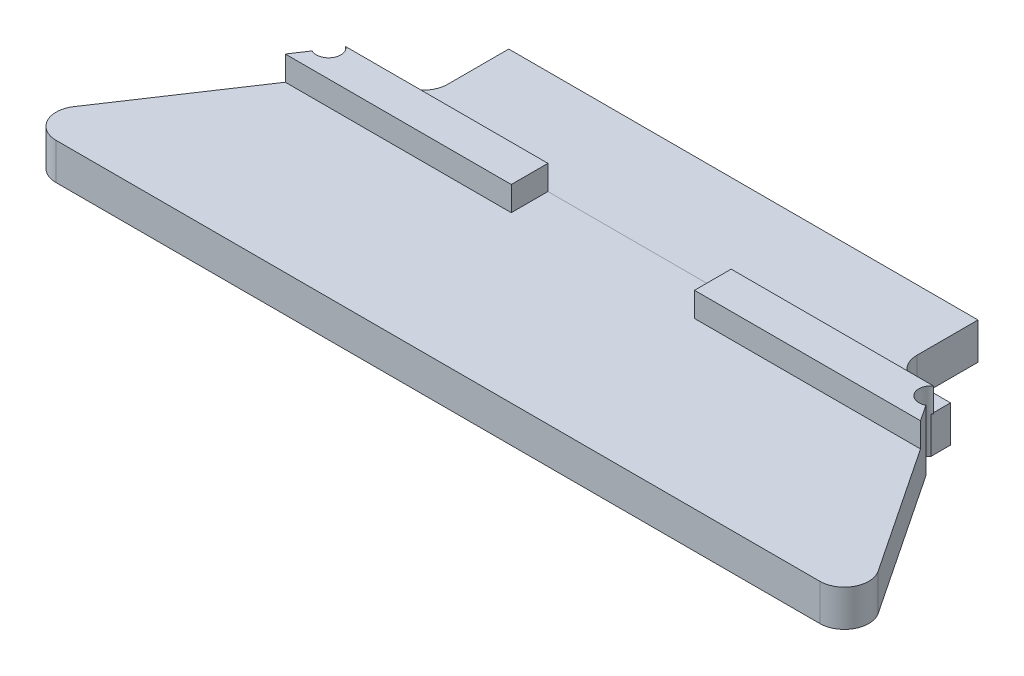
SolidWorks part; units mm, degrees
material "99.5% Aluminum Oxide"
ref_plane "Front Plane" through (0, 0, 0) normal (0, 0, 1) x (1, 0, 0)
ref_plane "Top Plane" through (0, 0, 0) normal (0, 1, 0) x (1, 0, 0)
ref_plane "Right Plane" through (0, 0, 0) normal (1, 0, 0) x (0, 0, -1)
sketch "Sketch1" plane through (0, 0, 0) normal (0, 1, 0) x (1, 0, 0)
  line L1 (-25, -12.5) -> (25, -12.5)
  line L2 (-25, -12.5) -> (-25, 12.5) construction
  line L3 (-25, 12.5) -> (25, 12.5) construction
  line L4 (25, -12.5) -> (25, 12.5) construction
  line L5 (-25, -12.5) -> (25, 12.5) construction
  line L6 (-25, 12.5) -> (25, -12.5) construction
  line L8 (-19.2062, 12.5) -> (19.2062, 12.5)
  line L11 (0, 11.2271) -> (0, -49988.7729) construction
  line L12 (-24.2062, 2.5) -> (-25, 2.5)
  line L13 (24.2062, 2.5) -> (25, 2.5)
  line L14 (-25, 2.5) -> (-35, -12.5)
  line L15 (-35, -12.5) -> (-25, -12.5)
  line L16 (25, 2.5) -> (35, -12.5)
  line L17 (35, -12.5) -> (25, -12.5)
  line L18 (-24.2062, 2.5) -> (-24.2062, 5.5)
  line L19 (-24.2062, 5.5) -> (-19.2062, 5.5)
  line L20 (-19.2062, 5.5) -> (-19.2062, 12.5)
  line L21 (24.2062, 2.5) -> (24.2062, 5.5)
  line L22 (24.2062, 5.5) -> (19.2062, 5.5)
  line L23 (19.2062, 5.5) -> (19.2062, 12.5)
  point P0 (0, 0)
  point P14 (0, 12.5)
  dimension "D1" = 25
  dimension "D2" = 50
  dimension "D3" = 10
  dimension "D4" = 15
  dimension "D5" = 0.7937
  dimension "D6" = 3
  dimension "D7" = 5
extrude "Boss-Extrude1" add sketch "Sketch1" along normal mid plane 3
sketch "Sketch4" plane through (0, 1.5, 0) normal (0, 1, 0) x (1, 0, 0)
  line L0 (-24.2062, 2.5) -> (-25, 2.5) construction
  line L2 (24.2062, 2.5) -> (23.9562, 2.5)
  line L3 (0, 0) -> (0, 50000) construction
  line L4 (-24.2062, 5.5) -> (-23.9562, 5.5)
  line L5 (-24.2062, 5.5) -> (-24.2062, 2.5)
  line L6 (-24.2062, 2.5) -> (-23.9562, 2.5)
  line L7 (-23.9562, 5.5) -> (-23.9562, 2.5)
  line L12 (23.9562, 5.5) -> (23.9562, 2.5)
  line L13 (24.2062, 5.5) -> (23.9562, 5.5)
  line L14 (24.2062, 5.5) -> (24.2062, 2.5)
  dimension "D1" = 0.25
extrude "Cut-Extrude4" cut sketch "Sketch4" against normal through all both and the other way through all
sketch "Sketch5" plane through (0, 1.5, 0) normal (0, 1, 0) x (1, 0, 0)
  line L0 (-23.9562, 2.5) -> (-24.6634, 3.2071) construction
  line L1 (-23.9562, 2.5) -> (-23.9562, 5.5) construction
  line L2 (-23.9562, 2.5) -> (-25, 2.5) construction
  line L3 (0, 0) -> (0, 50000) construction
  circle A0 centre (-24.6634, 3.2071) radius 1
  circle A1 centre (24.6634, 3.2071) radius 1
  point P2 (-23.9562, 3.9142)
  point P3 (-25.3705, 2.5)
  point P4 (-23.9562, 2.5)
  dimension "D1" = 2
  dimension "D2" = 45
extrude "Cut-Extrude5" cut sketch "Sketch5" against normal through all both and the other way through all
fillet "Fillet5" radius 2 4 edges at (35, 0, 12.5) (-35, 0, 12.5) (19.2062, 0, -5.5) (-19.2062, 0, -5.5)
sketch "Sketch6" plane through (0, 1.5, 0) normal (0, 1, 0) x (1, 0, 0)
  line L1 (-24.054, 4) -> (-7.5, 4)
  line L2 (-7.5, 4) -> (-7.5, 1)
  line L3 (-7.5, 1) -> (-26, 1)
  line L5 (-25.1213, 2.3181) -> (-26, 1)
  line L6 (-25.1213, 2.3181) -> (-32.9271, -9.3906) construction
  line L8 (32.9271, -9.3906) -> (25.1213, 2.3181) construction
  line L9 (26, 1) -> (25.1213, 2.3181)
  line L10 (24.054, 4) -> (7.5, 4)
  line L11 (7.5, 4) -> (7.5, 1)
  line L12 (7.5, 1) -> (26, 1)
  line L13 (19.2062, 12.5) -> (-19.2062, 12.5) construction
  arc A0 (-25.1213, 2.3181) -> (-23.9562, 3.9142) centre (-24.6634, 3.2071) ccw construction
  arc A1 (23.9562, 3.9142) -> (25.1213, 2.3181) centre (24.6634, 3.2071) ccw construction
  arc A2 (-24.054, 4) -> (-25.1213, 2.3181) centre (-24.6634, 3.2071) cw
  arc A3 (24.054, 4) -> (25.1213, 2.3181) centre (24.6634, 3.2071) ccw
  dimension "D1" = 8.5
  dimension "D2" = 15
  dimension "D3" = 3
extrude "Boss-Extrude2" add sketch "Sketch6" along normal blind 2
sketch "Sketch8" plane through (0, 1.5, 0) normal (0, 1, 0) x (1, 0, 0)
  line L0 (-7.5, 4) -> (-23.9562, 4) construction
  line L1 (-23.9562, 4) -> (-23.9562, 5.5) construction
  line L2 (-21.2062, 5.5) -> (-23.9562, 5.5) construction
  line L3 (-19.2062, 12.5) -> (-19.2062, 7.5) construction
  line L4 (19.2062, 12.5) -> (-19.2062, 12.5) construction
  line L5 (23.9562, 4) -> (7.5, 4) construction
  line L6 (23.9562, 5.5) -> (23.9562, 4) construction
  line L7 (23.9562, 5.5) -> (21.2062, 5.5) construction
  line L8 (19.2062, 7.5) -> (19.2062, 12.5) construction
  line L9 (-7.5, 4) -> (-23.9562, 4)
  line L10 (-23.9562, 4) -> (-23.9562, 5.5)
  line L11 (-21.2062, 5.5) -> (-23.9562, 5.5)
  line L12 (-19.2062, 12.5) -> (-19.2062, 7.5)
  line L13 (19.2062, 12.5) -> (-19.2062, 12.5)
  line L14 (23.9562, 4) -> (7.5, 4)
  line L15 (23.9562, 5.5) -> (23.9562, 4)
  line L16 (23.9562, 5.5) -> (21.2062, 5.5)
  line L17 (19.2062, 7.5) -> (19.2062, 12.5)
  line L18 (7.5, 4) -> (-7.5, 4)
  arc A0 (-21.2062, 5.5) -> (-19.2062, 7.5) centre (-21.2062, 7.5) ccw construction
  arc A1 (19.2062, 7.5) -> (21.2062, 5.5) centre (21.2062, 7.5) ccw construction
  arc A2 (-21.2062, 5.5) -> (-19.2062, 7.5) centre (-21.2062, 7.5) ccw
  arc A3 (19.2062, 7.5) -> (21.2062, 5.5) centre (21.2062, 7.5) ccw
split line "Split Line1"
sketch "Sketch9" plane through (0, -1.5, 0) normal (0, -1, 0) x (1, 0, 0)
  line L0 (24.054, -4) -> (7.5, -4) construction
  line L1 (24.054, -4) -> (7.5, -4)
  line L2 (-7.5, -4) -> (-24.054, -4) construction
  line L3 (-7.5, -4) -> (-24.054, -4)
  line L4 (32.9271, 9.3906) -> (25.1213, -2.3181) construction
  line L5 (-31.263, 12.5) -> (31.263, 12.5) construction
  line L6 (-25.1213, -2.3181) -> (-32.9271, 9.3906) construction
  line L7 (32.9271, 9.3906) -> (25.1213, -2.3181)
  line L8 (-31.263, 12.5) -> (31.263, 12.5)
  line L9 (-25.1213, -2.3181) -> (-32.9271, 9.3906)
  line L10 (-7.5, -4) -> (7.5, -4)
  arc A0 (-23.9562, -3.9142) -> (-25.1213, -2.3181) centre (-24.6634, -3.2071) ccw construction
  arc A1 (25.1213, -2.3181) -> (23.9562, -3.9142) centre (24.6634, -3.2071) ccw construction
  arc A2 (32.9271, 9.3906) -> (31.263, 12.5) centre (31.263, 10.5) ccw construction
  arc A3 (-31.263, 12.5) -> (-32.9271, 9.3906) centre (-31.263, 10.5) ccw construction
  arc A4 (-23.9562, -3.9142) -> (-25.1213, -2.3181) centre (-24.6634, -3.2071) ccw
  arc A5 (25.1213, -2.3181) -> (23.9562, -3.9142) centre (24.6634, -3.2071) ccw
  arc A6 (32.9271, 9.3906) -> (31.263, 12.5) centre (31.263, 10.5) ccw
  arc A7 (-31.263, 12.5) -> (-32.9271, 9.3906) centre (-31.263, 10.5) ccw
split line "Split Line2"
